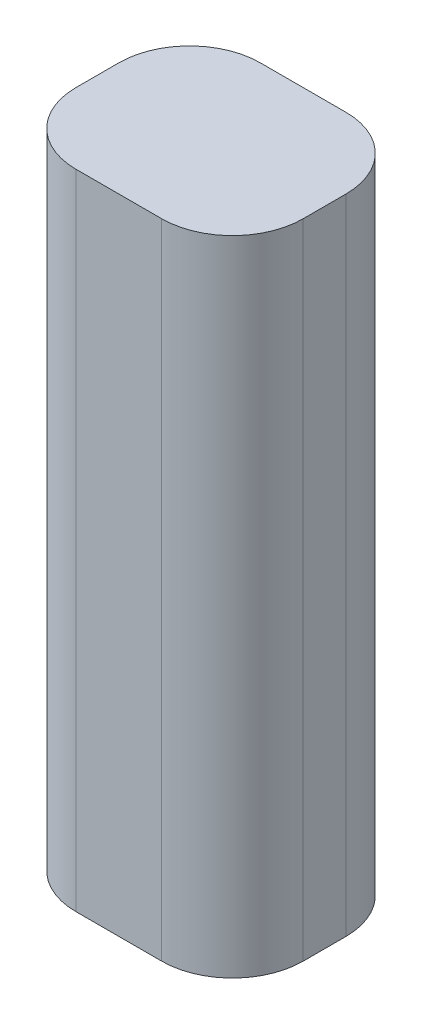
SolidWorks part; units mm, degrees
ref_plane "Front Plane" through (0, 0, 0) normal (0, 0, 1) x (1, 0, 0)
ref_plane "Top Plane" through (0, 0, 0) normal (0, 1, 0) x (1, 0, 0)
ref_plane "Right Plane" through (0, 0, 0) normal (1, 0, 0) x (0, 0, -1)
sketch "Sketch1" plane through (0, 0, 0) normal (0, 1, 0) x (1, 0, 0)
  line L0 (-1, -2.5) -> (1, -2.5) construction
  line L1 (3, -0.5) -> (3, 0.5) construction
  line L2 (1, 2.5) -> (-1, 2.5) construction
  line L3 (-3, 0.5) -> (-3, -0.5) construction
  line L4 (-1, -2.4) -> (1, -2.4)
  line L5 (2.9, -0.5) -> (2.9, 0.5)
  line L6 (1, 2.4) -> (-1, 2.4)
  line L7 (-2.9, 0.5) -> (-2.9, -0.5)
  line L8 (-2.65, 0.5) -> (-2.65, -0.5)
  line L9 (-1, -2.15) -> (1, -2.15)
  line L10 (2.65, -0.5) -> (2.65, 0.5)
  line L11 (1, 2.15) -> (-1, 2.15)
  arc A0 (1, -2.5) -> (3, -0.5) centre (1, -0.5) ccw construction
  arc A1 (3, 0.5) -> (1, 2.5) centre (1, 0.5) ccw construction
  arc A2 (-1, 2.5) -> (-3, 0.5) centre (-1, 0.5) ccw construction
  arc A3 (-3, -0.5) -> (-1, -2.5) centre (-1, -0.5) ccw construction
  arc A4 (1, -2.4) -> (2.9, -0.5) centre (1, -0.5) ccw
  arc A5 (2.9, 0.5) -> (1, 2.4) centre (1, 0.5) ccw
  arc A6 (-1, 2.4) -> (-2.9, 0.5) centre (-1, 0.5) ccw
  arc A7 (-2.9, -0.5) -> (-1, -2.4) centre (-1, -0.5) ccw
  arc A8 (-1, 2.15) -> (-2.65, 0.5) centre (-1, 0.5) ccw
  arc A9 (-2.65, -0.5) -> (-1, -2.15) centre (-1, -0.5) ccw
  arc A10 (1, -2.15) -> (2.65, -0.5) centre (1, -0.5) ccw
  arc A11 (2.65, 0.5) -> (1, 2.15) centre (1, 0.5) ccw
  point P13 (0, 2.5)
  point P15 (-3, 0)
  dimension "D1" = 2
  dimension "D4" = 3
  dimension "D2" = 1
  dimension "D3" = 2
  dimension "D5" = 3
  dimension "D6" = 0.1
  dimension "D7" = 0.25
extrude "Boss-Extrude3" add sketch "Sketch1" along normal blind 15 contours L10 A11 L11 A8 L8 A9 L9 A10
